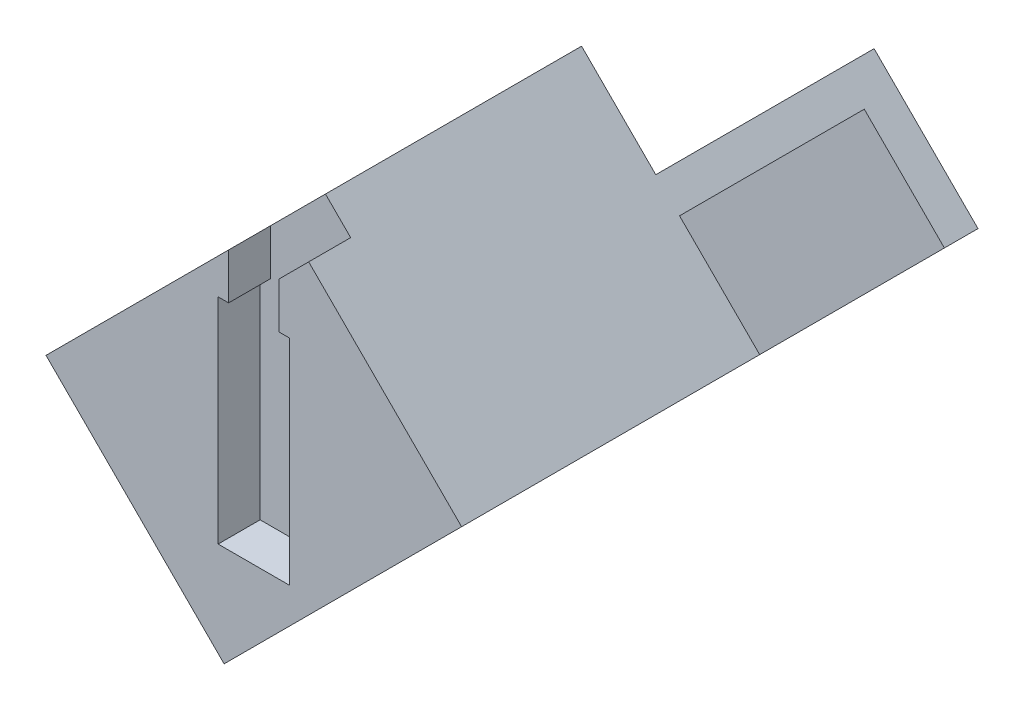
SolidWorks part; units mm, degrees
ref_plane "前视基准面" through (0, 0, 0) normal (0, 0, 1) x (1, 0, 0)
ref_plane "上视基准面" through (0, 0, 0) normal (0, 1, 0) x (1, 0, 0)
ref_plane "右视基准面" through (0, 0, 0) normal (1, 0, 0) x (0, 0, -1)
sketch "草图1" plane through (0, 0, 0) normal (0, 0, 1) x (1, 0, 0)
  line L0 (-16.9632, -12.75) -> (4.25, -33.9632)
  line L1 (0, 0) -> (8.5, 0)
  line L2 (0, 0) -> (0, -25.5)
  line L3 (0, -25.5) -> (8.5, -25.5)
  line L4 (8.5, 0) -> (8.5, -25.5)
  line L5 (4.25, -33.9632) -> (25.4632, -12.75)
  line L6 (25.4632, -12.75) -> (4.25, 8.4632)
  line L7 (4.25, 8.4632) -> (-16.9632, -12.75)
  line L8 (4.25, 8.4632) -> (4.25, -33.9632) construction
  line L9 (-16.9632, -12.75) -> (25.4632, -12.75) construction
  line L10 (4.25, 0) -> (4.25, -25.5) construction
  line L11 (0, -12.75) -> (8.5, -12.75) construction
  point P13 (4.25, -12.75)
  point P14 (4.25, -12.75)
  dimension "D1" = 8.5
  dimension "D2" = 25.5
  dimension "D3" = 30
  dimension "D4" = 45
  dimension "D5" = 90
  dimension "D6" = 30
extrude "凸台-拉伸1" add sketch "草图1" along normal blind 5
sketch "草图2" plane through (0, 0, 5) normal (0, 0, 1) x (1, 0, 0)
  line L0 (1.25, 0) -> (1.25, 5.4632)
  line L1 (8.5, 0) -> (0, 0) construction
  line L2 (4.25, 0) -> (4.25, -10.1779) construction
  line L3 (7.25, 0) -> (7.25, 5.4632)
  line L4 (4.25, -33.9632) -> (25.4632, -12.75)
  line L5 (25.4632, -12.75) -> (4.25, 8.4632)
  line L6 (4.25, 8.4632) -> (-16.9632, -12.75)
  line L7 (-16.9632, -12.75) -> (4.25, -33.9632)
  line L8 (4.25, -33.9632) -> (25.4632, -12.75)
  line L9 (25.4632, -12.75) -> (7.25, 5.4632)
  line L10 (1.25, 5.4632) -> (-16.9632, -12.75)
  line L11 (-16.9632, -12.75) -> (4.25, -33.9632)
  line L12 (7.25, 0) -> (8.5, 0)
  line L13 (0, 0) -> (1.25, 0)
  line L14 (0, 0) -> (0, -25.5)
  line L15 (0, -25.5) -> (8.5, -25.5)
  line L16 (8.5, 0) -> (8.5, -25.5)
  point P8 (4.25, 0)
  dimension "D2" = 3
  dimension "D1" = 0
extrude "凸台-拉伸2" add sketch "草图2" along normal blind 5 contours L0 L10 L11 L8 L9 L3 L12 L16 L15 L14 L13
sketch "草图3" plane through (0, 0, 5) normal (0, 0, 1) x (1, 0, 0)
  line L1 (0, 0) -> (8.5, 0)
  line L2 (0, 0) -> (0, -25.5)
  line L3 (0, -25.5) -> (8.5, -25.5)
  line L4 (8.5, 0) -> (8.5, -25.5)
extrude "凸台-拉伸3" add sketch "草图3" against normal blind 5
sketch "草图4" plane through (0, 0, 0) normal (0, 0, -1) x (-1, 0, 0)
  line L0 (12.7206, -12.75) -> (-4.25, 4.2206)
  line L1 (-4.25, 4.2206) -> (-21.2206, -12.75)
  line L2 (-21.2206, -12.75) -> (-4.25, -29.7206)
  line L3 (-4.25, -29.7206) -> (12.7206, -12.75)
  line L4 (-25.4632, -12.75) -> (-4.25, -33.9632)
  line L5 (-4.25, -33.9632) -> (16.9632, -12.75)
  line L6 (16.9632, -12.75) -> (-4.25, 8.4632)
  line L7 (-4.25, 8.4632) -> (-25.4632, -12.75)
  line L8 (-25.4632, -12.75) -> (-4.25, -33.9632)
  line L9 (-4.25, -33.9632) -> (16.9632, -12.75)
  line L10 (16.9632, -12.75) -> (-4.25, 8.4632)
  line L11 (-4.25, 8.4632) -> (-25.4632, -12.75)
  dimension "D1" = 0
  dimension "D2" = 3
extrude "凸台-拉伸4" add sketch "草图4" along normal blind 25.5
sketch "草图5" plane through (0, 0, 10) normal (0, 0, 1) x (1, 0, 0)
  line L0 (4.25, 8.4632) -> (25.4632, -12.75)
  line L1 (25.4632, -12.75) -> (28.9987, -9.2145)
  line L2 (28.9987, -9.2145) -> (7.7855, 11.9987)
  line L3 (7.7855, 11.9987) -> (4.25, 8.4632)
  line L4 (-16.9632, -12.75) -> (-20.4987, -16.2855)
  line L5 (-20.4987, -16.2855) -> (0.7145, -37.4987)
  line L6 (0.7145, -37.4987) -> (4.25, -33.9632)
  line L7 (4.25, -33.9632) -> (-16.9632, -12.75)
  dimension "D1" = 30
  dimension "D2" = 40
  dimension "D3" = 5
extrude "凸台-拉伸5" add sketch "草图5" against normal up to surface (35.5 mm away) up to face at (4.25, -12.75, -25.5)
sketch "草图6" plane through (0, 0, 10) normal (0, 0, 1) x (1, 0, 0)
  line L0 (7.25, 5.4632) -> (10.7855, 8.9987)
  line L1 (28.9987, -9.2145) -> (7.7855, 11.9987) construction
  line L2 (10.7855, 8.9987) -> (7.7855, 11.9987)
  line L3 (7.7855, 11.9987) -> (4.25, 8.4632)
  line L4 (4.25, 8.4632) -> (7.25, 5.4632)
extrude "切除-拉伸1" cut sketch "草图6" against normal up to surface (5 mm away) up to face at (4.25, -3.5123, 5)
sketch "草图7" plane through (0, 0, -25.5) normal (0, 0, -1) x (-1, 0, 0)
  line L0 (-4.25, 4.2206) -> (-7.7855, 7.7561)
  line L1 (-7.7855, 7.7561) -> (-24.7561, -9.2145)
  line L2 (-24.7561, -9.2145) -> (-21.2206, -12.75)
  line L3 (-21.2206, -12.75) -> (-4.25, 4.2206)
  line L4 (12.7206, -12.75) -> (16.2561, -16.2855)
  line L5 (16.2561, -16.2855) -> (-0.7145, -33.2561)
  line L6 (-0.7145, -33.2561) -> (-4.25, -29.7206)
  line L7 (-4.25, -29.7206) -> (12.7206, -12.75)
  line L8 (20.4987, -16.2855) -> (-7.7855, 11.9987) construction
  line L9 (-28.9987, -9.2145) -> (-7.7855, 11.9987) construction
  line L10 (20.4987, -16.2855) -> (-0.7145, -37.4987) construction
  dimension "D1" = 3
  dimension "D2" = 3
  dimension "D3" = 3
extrude "切除-拉伸2" cut sketch "草图7" against normal up to surface (25.5 mm away) up to face at (4.25, -12.75, 0)
sketch "草图8" plane through (9.8921, 9.8921, 0) normal (0.7071, 0.7071, 0) x (0, 0, -1)
  line L0 (25.5, -9.5208) -> (47.5, -9.5208)
  line L1 (25.5, -27.0208) -> (25.5, 2.9792) construction
  line L2 (47.5, -9.5208) -> (47.5, -13.5208)
  line L3 (47.5, -13.5208) -> (25.5, -13.5208)
  line L4 (25.5, -13.5208) -> (25.5, -9.5208)
  line L5 (25.5, 2.9792) -> (-5, 2.9792) construction
  dimension "D1" = 16.5
  dimension "D2" = 4
  dimension "D3" = 22
extrude "凸台-拉伸6" add sketch "草图8" against normal up to surface (40 mm away) up to face at (-9.8921, -26.8921, -7.75)
sketch "草图9" plane through (0, 0, -47.5) normal (0, 0, -1) x (-1, 0, 0)
  line L0 (-16.6244, 3.1599) -> (-28.9987, -9.2145)
  line L1 (-19.4528, 0.3315) -> (-16.6244, 3.1599) construction
  line L2 (-28.9987, -9.2145) -> (-0.7145, -37.4987)
  line L3 (-0.7145, -37.4987) -> (11.6599, -25.1244)
  line L4 (-19.4528, 0.3315) -> (8.8315, -27.9528)
  line L5 (8.8315, -27.9528) -> (11.6599, -25.1244)
  line L6 (11.6599, -25.1244) -> (-16.6244, 3.1599)
  line L7 (-16.6244, 3.1599) -> (-19.4528, 0.3315)
  line L10 (11.6599, -25.1244) -> (-16.6244, 3.1599)
  point P11 (-16.6695, 3.1148)
  dimension "D1" = 0
extrude "凸台-拉伸7" add sketch "草图9" along normal blind 4 contours L10 L0 L2 L3
sketch "草图10" plane through (9.5607, -9.5607, 0) normal (0.7071, -0.7071, 0) x (0, 0, -1)
  line L0 (25.5, -23.0104) -> (25.5, 10.9896) construction
  line L1 (25.5, 10.9896) -> (51.5, 10.9896)
  line L2 (25.5, 10.9896) -> (25.5, -23.0104)
  line L3 (25.5, -23.0104) -> (51.5, -23.0104)
  line L4 (51.5, 10.9896) -> (51.5, -23.0104)
  line L5 (51.5, 13.9896) -> (51.5, -26.0104) construction
  line L6 (25.5, 13.9896) -> (47.5, 13.9896) construction
  line L7 (25.5, -26.0104) -> (47.5, -26.0104) construction
  dimension "D1" = 3
  dimension "D2" = 3
extrude "切除-拉伸3" cut sketch "草图10" against normal blind 4
